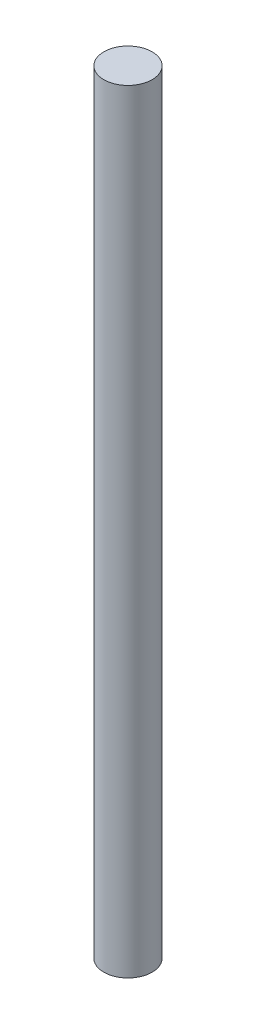
SolidWorks part; units mm, degrees
ref_plane "Front Plane" through (0, 0, 0) normal (0, 0, 1) x (1, 0, 0)
ref_plane "Top Plane" through (0, 0, 0) normal (0, 1, 0) x (1, 0, 0)
ref_plane "Right Plane" through (0, 0, 0) normal (1, 0, 0) x (0, 0, -1)
sketch "Sketch1" plane through (0, 0, 0) normal (0, 1, 0) x (1, 0, 0)
  circle A0 centre (0, 0) radius 12.5
  dimension "D1" = 25
extrude "Boss-Extrude1" add sketch "Sketch1" along normal mid plane 400
equation "\"a\"= 1"
equation "\"b\"= 1"
equation "\"c\"= 1"
equation "\"d\"= 1"
equation "\"e\"= 1"
equation "\"x\"= 1"
equation "\"y\"= 1"
equation "\"z\"= 1"
